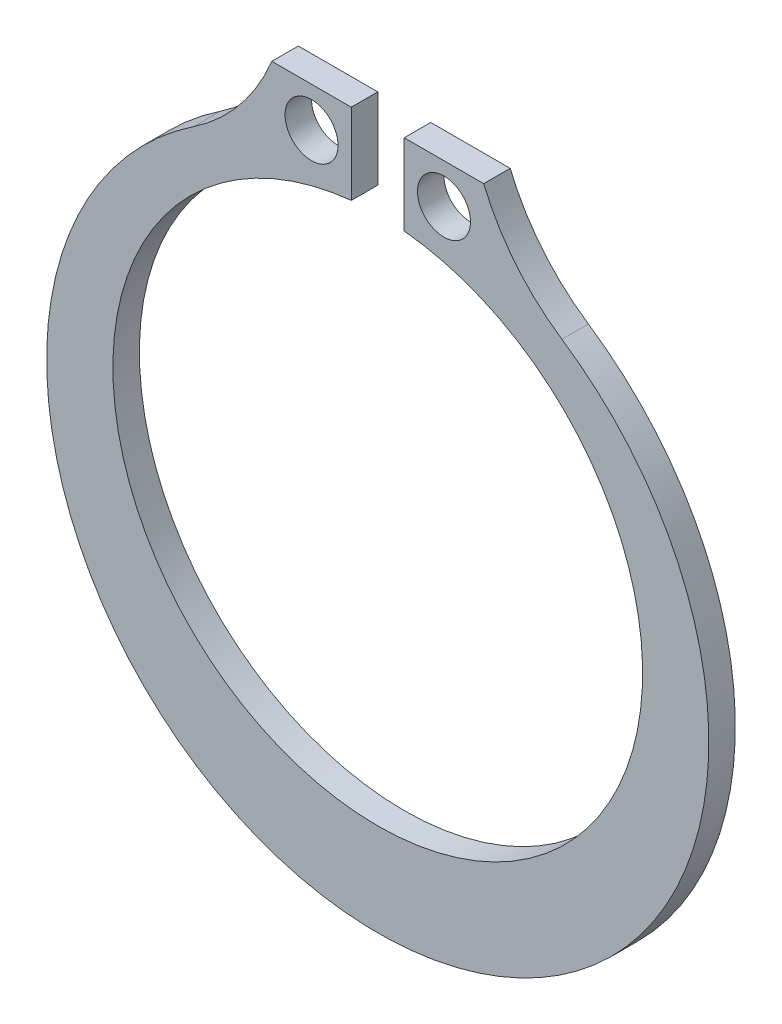
SolidWorks part; units mm, degrees
material "Alloy Steel"
ref_plane "Front Plane" through (0, 0, 0) normal (0, 0, 1) x (1, 0, 0)
ref_plane "Top Plane" through (0, 0, 0) normal (0, 1, 0) x (1, 0, 0)
ref_plane "Right Plane" through (0, 0, 0) normal (1, 0, 0) x (0, 0, -1)
sketch "Sketch1" plane through (0, 0, 0) normal (0, 0, 1) x (1, 0, 0)
  line L0 (0, 0) -> (0, 10.3048) construction
  line L1 (-4, 14) -> (-1, 14)
  line L2 (-1, 14) -> (-1, 10.9499)
  line L3 (1, 14) -> (1, 10.9499)
  line L4 (4, 14) -> (1, 14)
  arc A0 (-6.9519, 10.3885) -> (6.9519, 10.3885) centre (0, 0) ccw
  arc A2 (-1, 10.9499) -> (1, 10.9499) centre (0, 1) ccw
  arc A3 (-4, 14) -> (-6.9519, 10.3885) centre (-11.401, 17.0372) cw
  arc A4 (4, 14) -> (6.9519, 10.3885) centre (11.401, 17.0372) ccw
  circle A5 centre (-2.5, 12.5) radius 1
  circle A7 centre (2.5, 12.5) radius 1
  dimension "D1" = 25
  dimension "D2" = 20
  dimension "D4" = 8
  dimension "D8" = 2
  dimension "D9" = 1.5
  dimension "D3" = 1
  dimension "D5" = 13
  dimension "D6" = 8
  dimension "D7" = 2
  dimension "D10" = 1.5
extrude "Boss-Extrude1" add sketch "Sketch1" along normal blind 1
